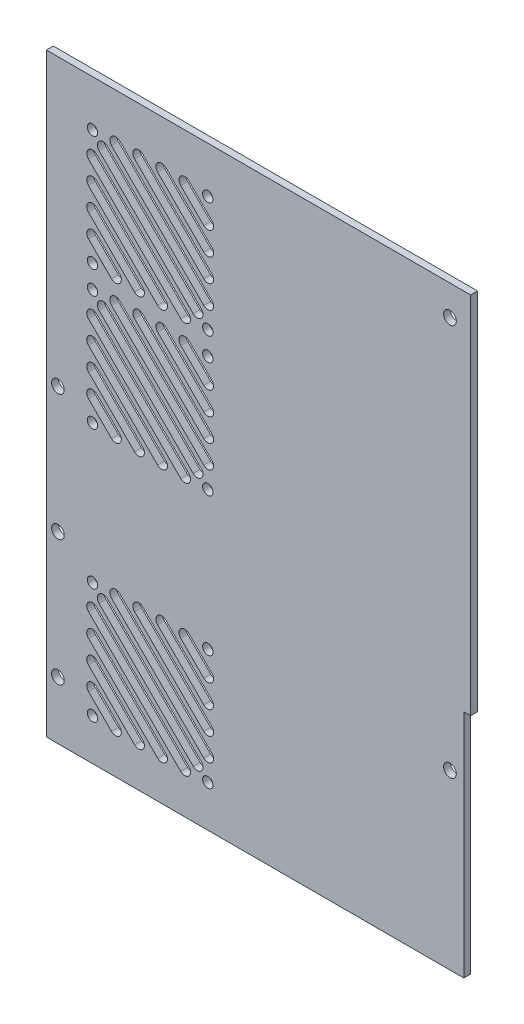
SolidWorks part; units mm, degrees
ref_plane "Front Plane" through (0, 0, 0) normal (0, 0, 1) x (1, 0, 0)
ref_plane "Top Plane" through (0, 0, 0) normal (0, 1, 0) x (1, 0, 0)
ref_plane "Right Plane" through (0, 0, 0) normal (1, 0, 0) x (0, 0, -1)
sketch "Sketch1" plane through (0, 0, 0) normal (0, 0, 1) x (1, 0, 0)
  line L1 (0, 0) -> (184, 0)
  line L2 (0, 0) -> (0, 258)
  line L3 (0, 258) -> (184, 258)
  line L4 (184, 0) -> (184, 258)
  dimension "D1" = 184
  dimension "D2" = 258
extrude "Boss-Extrude1" add sketch "Sketch1" along normal blind 3
sketch "Sketch2" plane through (0, 0, 0) normal (0, 0, -1) x (-1, 0, 0)
  line L0 (-175, 75) -> (-175, 245)
  circle A0 centre (-175, 75) radius 1.7 construction
  circle A1 centre (-5, 134.225) radius 2.2 construction
  circle A2 centre (-5, 79.6125) radius 2.2 construction
  circle A3 centre (-175, 75) radius 1.7
  circle A4 centre (-5, 134.225) radius 2.2
  circle A5 centre (-5, 79.6125) radius 2.2
  circle A6 centre (-5, 25) radius 2.15 construction
  circle A7 centre (-5, 25) radius 2.15
  point P0 (-175, 75)
  point P2 (-5, 134.225)
  point P4 (-5, 79.6125)
  point P11 (-175, 245)
  point P19 (-5, 25)
  dimension "D1" = 170
hole_wizard "M5 Clearance Hole1" positions "Sketch2" profile "Sketch3" hole size "M5" standard "ANSI Metric" end condition through all
sketch "Sketch3" plane through (175, 75, 0) normal (1, 0, 0) x (0, 1, 0)
  line L0 (0, 0) -> (0, 3)
  line L1 (0, 3) -> (2.75, 3)
  line L2 (2.75, 3) -> (2.75, 0)
  line L5 (2.75, 0) -> (0, 0)
  line L11 (0, -6.35) -> (0, 107.95) construction
  dimension "Thru Hole Dia." = 5.5
  dimension "Thru Hole Depth" = 3
sketch "Sketch4" plane through (0, 0, 0) normal (0, 0, -1) x (-1, 0, 0)
  line L1 (-70, 238) -> (-20, 238) construction
  line L2 (-70, 238) -> (-70, 188) construction
  line L3 (-70, 188) -> (-20, 188) construction
  line L4 (-20, 238) -> (-20, 188) construction
  line L5 (0, 258) -> (0, 0) construction
  line L6 (-184, 258) -> (0, 258) construction
  line L7 (-60, 238) -> (-70, 228) construction
  line L8 (-50, 238) -> (-70, 218) construction
  line L9 (-40, 238) -> (-70, 208) construction
  line L10 (-30, 238) -> (-70, 198) construction
  line L11 (-20, 238) -> (-70, 188) construction
  line L12 (-20, 228) -> (-60, 188) construction
  line L13 (-20, 218) -> (-50, 188) construction
  line L14 (-20, 208) -> (-40, 188) construction
  line L15 (-20, 198) -> (-30, 188) construction
  line L16 (-60, 238) -> (-70, 228) construction
  line L17 (-58.2322, 236.2322) -> (-68.2322, 226.2322)
  line L18 (-61.7678, 239.7678) -> (-71.7678, 229.7678)
  line L19 (-50, 238) -> (-70, 218) construction
  line L20 (-48.2322, 236.2322) -> (-68.2322, 216.2322)
  line L21 (-51.7678, 239.7678) -> (-71.7678, 219.7678)
  line L22 (-40, 238) -> (-70, 208) construction
  line L23 (-38.2322, 236.2322) -> (-68.2322, 206.2322)
  line L24 (-41.7678, 239.7678) -> (-71.7678, 209.7678)
  line L25 (-30, 238) -> (-70, 198) construction
  line L26 (-28.2322, 236.2322) -> (-68.2322, 196.2322)
  line L27 (-31.7678, 239.7678) -> (-71.7678, 199.7678)
  line L28 (-65.4038, 192.5962) -> (-24.5962, 233.4038) construction
  line L29 (-67.1716, 194.364) -> (-26.364, 235.1716)
  line L30 (-63.636, 190.8284) -> (-22.8284, 231.636)
  line L31 (-20, 228) -> (-60, 188) construction
  line L32 (-18.2322, 226.2322) -> (-58.2322, 186.2322)
  line L33 (-21.7678, 229.7678) -> (-61.7678, 189.7678)
  line L34 (-50, 188) -> (-20, 218) construction
  line L35 (-51.7678, 189.7678) -> (-21.7678, 219.7678)
  line L36 (-48.2322, 186.2322) -> (-18.2322, 216.2322)
  line L37 (-20, 208) -> (-40, 188) construction
  line L38 (-18.2322, 206.2322) -> (-38.2322, 186.2322)
  line L39 (-21.7678, 209.7678) -> (-41.7678, 189.7678)
  line L40 (-20, 198) -> (-30, 188) construction
  line L41 (-18.2322, 196.2322) -> (-28.2322, 186.2322)
  line L42 (-21.7678, 199.7678) -> (-31.7678, 189.7678)
  circle A0 centre (-70, 238) radius 4
  circle A1 centre (-20, 238) radius 4
  circle A2 centre (-70, 188) radius 4
  circle A3 centre (-20, 188) radius 3
  arc A4 (-58.2322, 236.2322) -> (-61.7678, 239.7678) centre (-60, 238) ccw
  arc A5 (-71.7678, 229.7678) -> (-68.2322, 226.2322) centre (-70, 228) ccw
  arc A6 (-48.2322, 236.2322) -> (-51.7678, 239.7678) centre (-50, 238) ccw
  arc A7 (-71.7678, 219.7678) -> (-68.2322, 216.2322) centre (-70, 218) ccw
  arc A8 (-38.2322, 236.2322) -> (-41.7678, 239.7678) centre (-40, 238) ccw
  arc A9 (-71.7678, 209.7678) -> (-68.2322, 206.2322) centre (-70, 208) ccw
  arc A10 (-28.2322, 236.2322) -> (-31.7678, 239.7678) centre (-30, 238) ccw
  arc A11 (-71.7678, 199.7678) -> (-68.2322, 196.2322) centre (-70, 198) ccw
  arc A12 (-67.1716, 194.364) -> (-63.636, 190.8284) centre (-65.4038, 192.5962) ccw
  arc A13 (-22.8284, 231.636) -> (-26.364, 235.1716) centre (-24.5962, 233.4038) ccw
  arc A14 (-18.2322, 226.2322) -> (-21.7678, 229.7678) centre (-20, 228) ccw
  arc A15 (-61.7678, 189.7678) -> (-58.2322, 186.2322) centre (-60, 188) ccw
  arc A16 (-51.7678, 189.7678) -> (-48.2322, 186.2322) centre (-50, 188) ccw
  arc A17 (-18.2322, 216.2322) -> (-21.7678, 219.7678) centre (-20, 218) ccw
  arc A18 (-18.2322, 206.2322) -> (-21.7678, 209.7678) centre (-20, 208) ccw
  arc A19 (-41.7678, 189.7678) -> (-38.2322, 186.2322) centre (-40, 188) ccw
  arc A20 (-18.2322, 196.2322) -> (-21.7678, 199.7678) centre (-20, 198) ccw
  arc A21 (-31.7678, 189.7678) -> (-28.2322, 186.2322) centre (-30, 188) ccw
  point P28 (-65, 233)
  point P33 (-60, 228)
  point P38 (-55, 223)
  point P43 (-50, 218)
  point P50 (-45, 213)
  point P55 (-40, 208)
  point P60 (-35, 203)
  point P65 (-30, 198)
  point P70 (-25, 193)
  dimension "D14" = 8
  dimension "D15" = 8
  dimension "D16" = 8
  dimension "D17" = 6
  dimension "D18" = 2.5
  dimension "D19" = 2.5
  dimension "D20" = 2.5
  dimension "D21" = 2.5
  dimension "D22" = 2.5
  dimension "D23" = 2.5
  dimension "D24" = 2.5
  dimension "D25" = 2.5
  dimension "D26" = 2.5
  dimension "D1" = 50
  dimension "D2" = 50
  dimension "D3" = 20
  dimension "D4" = 20
  dimension "D5" = 45
  dimension "D6" = 10
  dimension "D7" = 10
  dimension "D8" = 10
  dimension "D9" = 10
  dimension "D10" = 10
  dimension "D11" = 10
  dimension "D12" = 10
  dimension "D13" = 10
extrude "Cut-Extrude1" cut sketch "Sketch4" against normal blind 10 contours L18 A5 L17 A4 | L21 A7 L20 A6 | L24 A9 L23 A8 | L27 A11 L26 A10 | A13 L29 A12 L30 | L33 A15 L32 A14 | L36 A17 L35 A16 | L39 A19 L38 A18 | L42 A21 L41 A20
sketch "Sketch5" plane through (0, 0, 0) normal (0, 0, -1) x (-1, 0, 0)
  point P0 (-20, 188)
  point P2 (-70, 188)
  point P4 (-70, 238)
  point P6 (-20, 238)
hole_wizard "M4 Clearance Hole1" positions "Sketch5" profile "Sketch6" hole size "M4" standard "ANSI Metric" end condition through all
sketch "Sketch6" plane through (20, 188, 0) normal (1, 0, 0) x (0, 1, 0)
  line L0 (0, 0) -> (0, 3)
  line L1 (0, 3) -> (2.25, 3)
  line L2 (2.25, 3) -> (2.25, 0)
  line L5 (2.25, 0) -> (0, 0)
  line L11 (0, -6.35) -> (0, 107.95) construction
  dimension "Thru Hole Dia." = 4.5
  dimension "Thru Hole Depth" = 3
pattern_linear "LPattern1" count 2 spacing 60 along (0, -1, 0) of "Cut-Extrude1", "M4 Clearance Hole1"
pattern_linear "LPattern2" count 2 spacing 170 along (0, -1, 0) of "M4 Clearance Hole1", "Cut-Extrude1"
sketch "Sketch7" plane through (0, 0, 0) normal (0, 0, -1) x (-1, 0, 0)
  line L0 (0, 0) -> (-184, 0) construction
  line L1 (-184, 0) -> (-181, 0)
  line L2 (-184, 0) -> (-184, 100)
  line L3 (-184, 100) -> (-181, 100)
  line L4 (-181, 0) -> (-181, 100)
  line L5 (-184, 0) -> (-184, 258) construction
  dimension "D1" = 3
  dimension "D2" = 100
extrude "Cut-Extrude2" cut sketch "Sketch7" against normal blind 10
